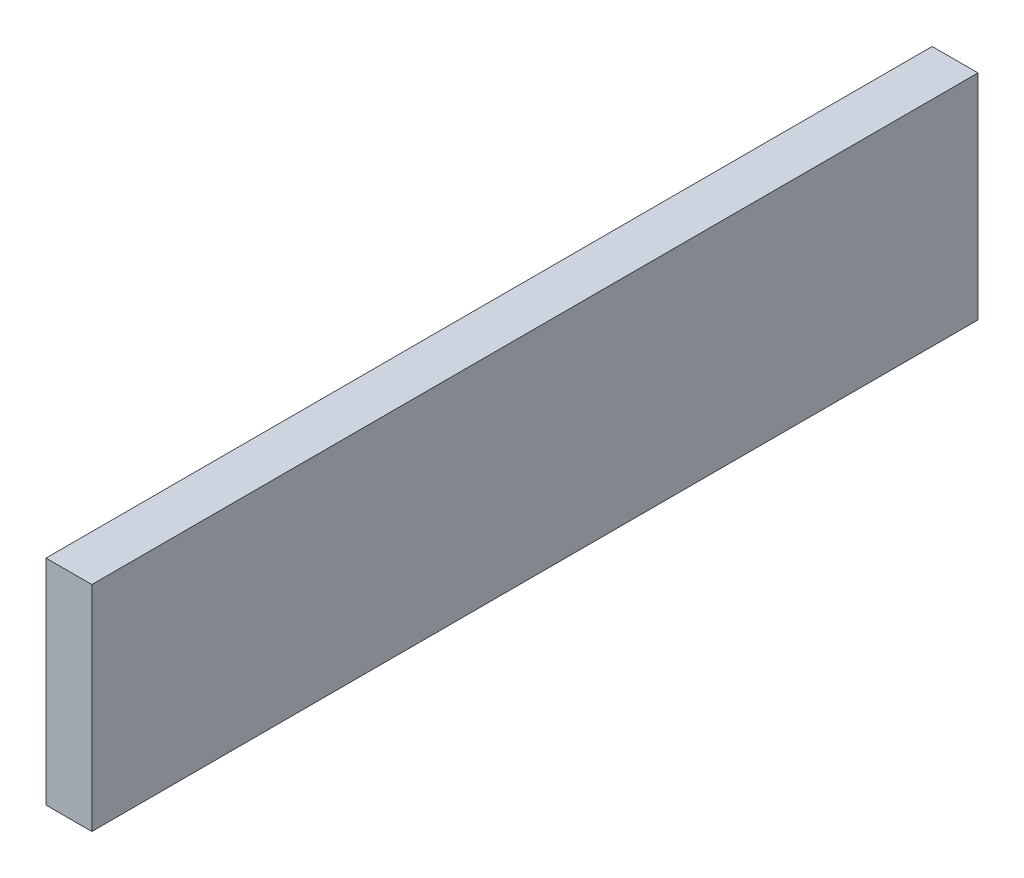
SolidWorks part; units mm, degrees
ref_plane "Plan de face" through (0, 0, 0) normal (0, 0, 1) x (1, 0, 0)
ref_plane "Plan de dessus" through (0, 0, 0) normal (0, 1, 0) x (1, 0, 0)
ref_plane "Plan de droite" through (0, 0, 0) normal (1, 0, 0) x (0, 0, -1)
sketch "Esquisse1" plane through (0, 0, 0) normal (0, 0, 1) x (1, 0, 0)
  line L0 (0, 0) -> (-30, 0)
  line L1 (0, 0) -> (350, 0)
  line L2 (0, 0) -> (0, 30)
  line L3 (0, 30) -> (350, 30)
  line L4 (350, 0) -> (350, 30)
  line L5 (350, 30) -> (380, 30)
  line L6 (350, 30) -> (350, 170)
  line L7 (350, 170) -> (380, 170)
  line L8 (380, 30) -> (380, 170)
  line L9 (0, 30) -> (-30, 30)
  line L10 (0, 30) -> (0, 170)
  line L11 (0, 170) -> (-30, 170)
  line L12 (-30, 30) -> (-30, 170)
  line L13 (-30, 0) -> (-30, 30)
  line L14 (350, 0) -> (380, 0)
  line L15 (380, 0) -> (380, 30)
  line L16 (350, 170) -> (380, 152.6815)
  line L17 (380, 152.6815) -> (380, 170)
  line L18 (380, 170) -> (380, 187.3215)
  line L19 (350, 170) -> (380, 187.3215)
  line L20 (-30, 170) -> (0, 152.6815)
  line L21 (0, 170) -> (0, 187.3215)
  line L22 (0, 187.3215) -> (-30, 170)
  line L23 (0, 170) -> (-30, 152.6815)
  line L24 (-30, 152.6815) -> (-30, 187.3185)
  line L25 (-30, 187.3185) -> (0, 170)
  dimension "D1" = 30
  dimension "D2" = 350
  dimension "D3" = 30
  dimension "D4" = 30
  dimension "D5" = 140
  dimension "D6" = 140
  dimension "D7" = 34.64
  dimension "D8" = 34.64
  dimension "D9" = 34.6415
  dimension "D10" = 34.64
  dimension "D11" = 34.64
  dimension "D12" = 34.64
  dimension "D13" = 34.64
  dimension "D14" = 34.637
extrude "Boss.-Extru.1" add sketch "Esquisse1" along normal blind 580 contours L16 L6 L5 L8 | L7 L16 L8 | L23 L24 L25 | L11 | L4 | L3
